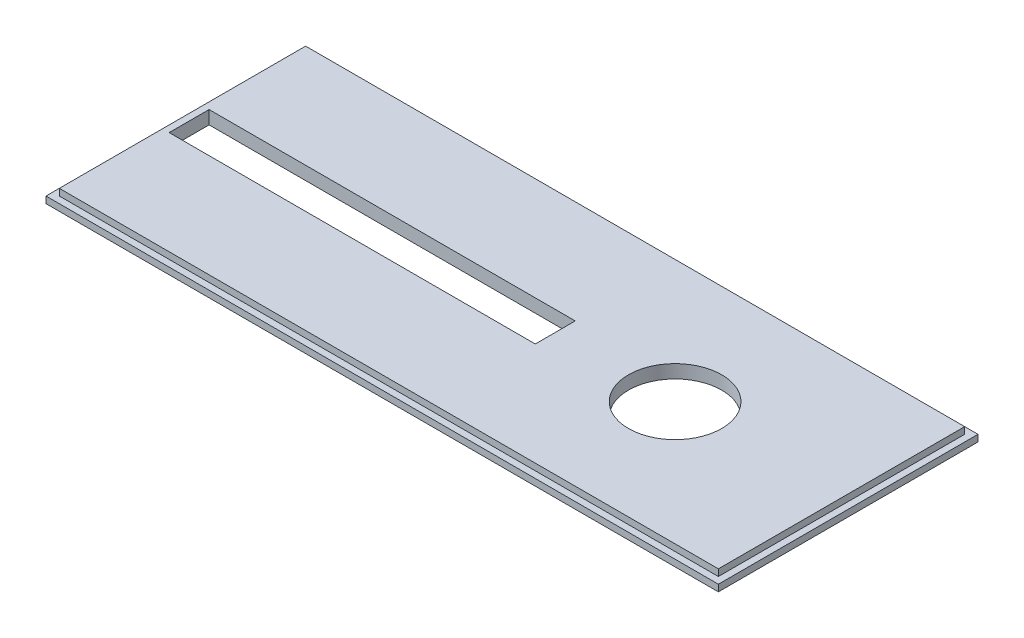
SolidWorks part; units mm, degrees
ref_plane "Front Plane" through (0, 0, 0) normal (0, 0, 1) x (1, 0, 0)
ref_plane "Top Plane" through (0, 0, 0) normal (0, 1, 0) x (1, 0, 0)
ref_plane "Right Plane" through (0, 0, 0) normal (1, 0, 0) x (0, 0, -1)
sketch "Sketch2" plane through (0, 0, 0) normal (0, 1, 0) x (1, 0, 0)
  line L1 (0, 0) -> (101, 0)
  line L2 (0, 0) -> (0, 39)
  line L3 (0, 39) -> (101, 39)
  line L4 (101, 0) -> (101, 39)
extrude "Boss-Extrude1" add sketch "Sketch2" along normal blind 1
sketch "Sketch3" plane through (0, 1, 0) normal (0, 1, 0) x (1, 0, 0)
  line L3 (1, 1) -> (100, 1)
  line L4 (100, 1) -> (100, 38)
  line L5 (100, 38) -> (1, 38)
  line L6 (1, 38) -> (1, 1)
extrude "Boss-Extrude2" add sketch "Sketch3" along normal blind 1
sketch "Sketch4" plane through (0, 2, 0) normal (0, 1, 0) x (1, 0, 0)
  line L0 (1, 19.5) -> (2, 19.5) construction
  line L1 (1, 38) -> (1, 1) construction
  line L2 (2, 19.5) -> (2, 22.5)
  line L3 (2, 22.5) -> (57, 22.5)
  line L4 (57, 22.5) -> (57, 16.5)
  line L5 (57, 16.5) -> (2, 16.5)
  line L6 (2, 16.5) -> (2, 19.5)
  line L7 (100, 19.5) -> (75, 19.5) construction
  line L8 (100, 1) -> (100, 38) construction
  circle A0 centre (75, 19.5) radius 7
extrude "Cut-Extrude1" cut sketch "Sketch4" against normal blind 2
sketch "Sketch5" plane through (0, 0, 0) normal (0, -1, 0) x (1, 0, 0)
  line L0 (4.9282, -11.6437) -> (53.8241, -11.6437) construction
  text T0 "<b>ECE 196 VU Meter</b>\r\n" font "Century Gothic" height in points 15
extrude "Cut-Extrude2" cut sketch "Sketch5" against normal blind 0.2
